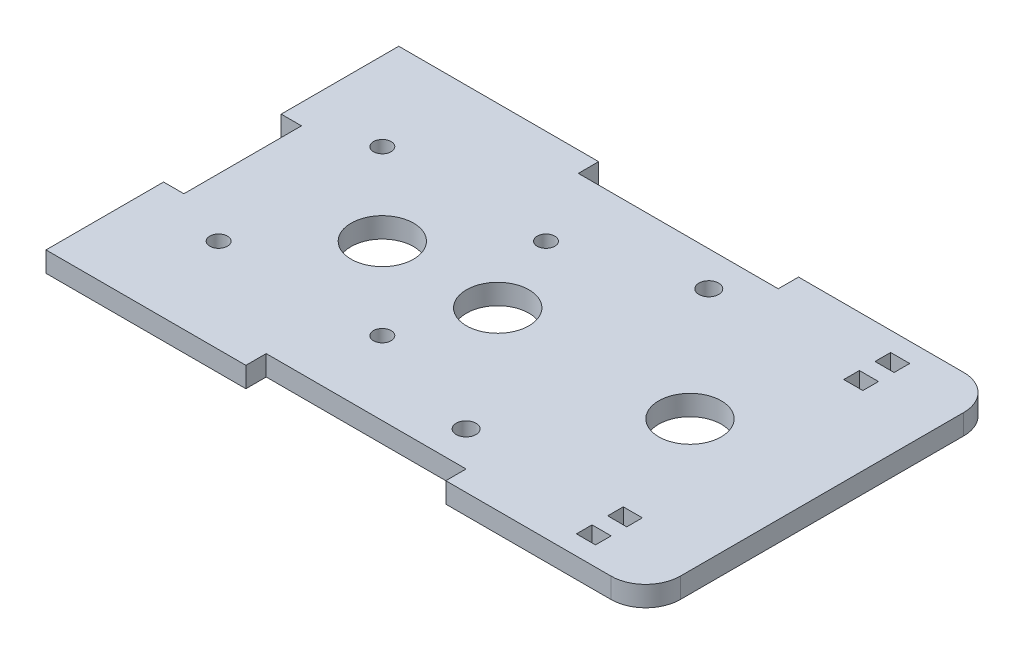
SolidWorks part; units mm, degrees
ref_plane "Front Plane" through (0, 0, 0) normal (0, 0, 1) x (1, 0, 0)
ref_plane "Top Plane" through (0, 0, 0) normal (0, 1, 0) x (1, 0, 0)
ref_plane "Right Plane" through (0, 0, 0) normal (1, 0, 0) x (0, 0, -1)
sketch "Sketch1" plane through (0, 0, 0) normal (0, 1, 0) x (1, 0, 0)
  line L1 (-86.36, -50.8) -> (86.36, -50.8)
  line L2 (-86.36, -50.8) -> (-86.36, 50.8)
  line L3 (-86.36, 50.8) -> (86.36, 50.8)
  line L4 (86.36, -50.8) -> (86.36, 50.8)
  line L5 (-86.36, -50.8) -> (86.36, 50.8) construction
  line L6 (-86.36, 50.8) -> (86.36, -50.8) construction
  point P0 (0, 0)
  dimension "D1" = 172.72
  dimension "D2" = 101.6
extrude "Boss-Extrude1" add sketch "Sketch1" along normal blind 5.85
sketch "Sketch4" plane through (0, 5.85, 0) normal (0, 1, 0) x (1, 0, 0)
  line L0 (-86.36, 50.8) -> (-86.36, -50.8) construction
  line L1 (-86.36, 16.9333) -> (-80.51, 16.9333)
  line L2 (-86.36, 16.9333) -> (-86.36, -16.9333)
  line L3 (-86.36, -16.9333) -> (-80.51, -16.9333)
  line L4 (-80.51, 16.9333) -> (-80.51, -16.9333)
  line L5 (-86.36, -50.8) -> (86.36, -50.8) construction
  line L6 (-28.7867, -50.8) -> (28.7867, -50.8)
  line L7 (-28.7867, -50.8) -> (-28.7867, -44.95)
  line L8 (-28.7867, -44.95) -> (28.7867, -44.95)
  line L9 (28.7867, -50.8) -> (28.7867, -44.95)
  line L10 (86.36, 50.8) -> (-86.36, 50.8) construction
  line L11 (-28.7867, 50.8) -> (28.7867, 50.8)
  line L12 (-28.7867, 50.8) -> (-28.7867, 44.95)
  line L13 (-28.7867, 44.95) -> (28.7867, 44.95)
  line L14 (28.7867, 50.8) -> (28.7867, 44.95)
  line L15 (-28.7867, 44.95) -> (-28.7867, -44.95) construction
  line L16 (28.7867, 44.95) -> (28.7867, -44.95) construction
  line L17 (60.86, 40.75) -> (60.86, -40.75) construction
  line L18 (60.86, 45.25) -> (66.36, 45.25)
  line L19 (60.86, 45.25) -> (60.86, 40.75)
  line L20 (60.86, 40.75) -> (66.36, 40.75)
  line L21 (86.36, -50.8) -> (86.36, 50.8) construction
  line L22 (60.86, -45.25) -> (66.36, -45.25)
  line L23 (60.86, -45.25) -> (60.86, -40.75)
  line L24 (60.86, -40.75) -> (66.36, -40.75)
  line L25 (60.86, -31.75) -> (66.36, -31.75)
  line L26 (60.86, -31.75) -> (60.86, -36.25)
  line L27 (60.86, -36.25) -> (66.36, -36.25)
  line L28 (66.36, -40.75) -> (66.36, -45.25)
  line L29 (66.36, -31.75) -> (66.36, -36.25)
  line L30 (60.86, 36.25) -> (66.36, 36.25)
  line L31 (60.86, 36.25) -> (60.86, 31.75)
  line L32 (66.36, -40.75) -> (66.36, 40.75) construction
  line L33 (60.86, 31.75) -> (66.36, 31.75)
  line L34 (66.36, 36.25) -> (66.36, 31.75)
  line L35 (66.36, 40.75) -> (66.36, 45.25)
  dimension "D1" = 5.85
  dimension "D2" = 5.85
  dimension "D3" = 5.85
  dimension "D4" = 57.5733
  dimension "D5" = 57.5733
  dimension "D6" = 33.8667
  dimension "D7" = 33.8667
  dimension "D8" = 5.5
  dimension "D9" = 5.55
  dimension "D10" = 5.55
  dimension "D11" = 4.5
  dimension "D12" = 4.5
  dimension "D13" = 4.5
  dimension "D14" = 4.5
  dimension "D15" = 4.5
  dimension "D16" = 4.5
  dimension "D17" = 20
extrude "Cut-Extrude5" cut sketch "Sketch4" against normal blind 10
sketch "Sketch5" plane through (0, 0, 0) normal (0, 1, 0) x (1, 0, 0)
  line L0 (-86.36, -0.1894) -> (2.54, -0.1894) construction
  line L2 (2.54, -0.1894) -> (91.44, -0.1894) construction
  line L4 (0, 50.8) -> (0, -50.8) construction
  line L7 (-6.8721, -0.1894) -> (-40.1037, -0.1894) construction
  line L8 (48.5139, -0.1894) -> (-6.8721, -0.1894) construction
  line L9 (-49.1037, -0.1894) -> (-40.1037, -9.1894) construction
  line L10 (-40.1037, -9.1894) -> (-31.1037, -0.1894) construction
  line L11 (-31.1037, -0.1894) -> (-40.1037, 8.8106) construction
  line L12 (-40.1037, 8.8106) -> (-49.1037, -0.1894) construction
  line L13 (-86.36, 16.9333) -> (-86.36, -0.1894) construction
  line L21 (-63.6769, -23.7626) -> (-16.5306, -23.7626) construction
  line L22 (-63.6769, -23.7626) -> (-63.6769, 23.3837) construction
  line L23 (-63.6769, 23.3837) -> (-16.5306, 23.3837) construction
  line L24 (-16.5306, -23.7626) -> (-16.5306, 23.3837) construction
  line L25 (-63.6769, -23.7626) -> (-16.5306, 23.3837) construction
  line L26 (-63.6769, 23.3837) -> (-16.5306, -23.7626) construction
  line L29 (26.7151, -50.8) -> (26.7151, 50.8) construction
  line L30 (-63.6769, 23.3837) -> (-63.6769, 25.9237) construction
  circle A1 centre (-6.8721, -0.1894) radius 9
  circle A2 centre (-40.1037, -0.1894) radius 9
  circle A3 centre (-63.6769, 23.3837) radius 2.54
  circle A4 centre (-16.5306, 23.3837) radius 2.54
  circle A5 centre (-63.6769, -23.7626) radius 2.54
  circle A6 centre (-16.5306, -23.7626) radius 2.54
  circle A7 centre (48.5139, -0.1894) radius 9
  dimension "D1" = 18
  dimension "D2" = 18
  dimension "D3" = 18
  dimension "D5" = 55.386
  dimension "D6" = 33.2317
  dimension "D7" = 46.2563
extrude "Cut-Extrude10" cut sketch "Sketch5" along direction (0, -1, 0) on the side of the normal blind 16
fillet "Fillet1" radius 10 2 edges at (86.36, 2.925, -50.8) (86.36, 2.925, 50.8)
sketch "Sketch6" plane through (0, 5.85, 0) normal (0, 1, 0) x (1, 0, 0)
  line L0 (28.7867, -44.95) -> (28.7867, -34.95) construction
  line L1 (28.7867, -34.95) -> (18.7867, -34.95) construction
  line L2 (28.7867, 44.95) -> (28.7867, 34.95) construction
  line L3 (28.7867, 34.95) -> (18.7867, 34.95) construction
  circle A0 centre (18.7867, -34.95) radius 2.85
  circle A1 centre (18.7867, 34.95) radius 2.85
  dimension "D1" = 5.7
  dimension "D4" = 5.7
  dimension "D2" = 10
  dimension "D3" = 10
  dimension "D5" = 10
  dimension "D6" = 10
extrude "Cut-Extrude11" cut sketch "Sketch6" against normal blind 10
equation "\"D1@Sketch1\" = \"Length@RudderBox.SLDASM\""
equation "\"D2@Sketch1\" = \"Width@RudderBox.SLDASM\""
equation "\"D1@Boss-Extrude1\" = \"Material@RudderBox.SLDASM\""
equation "\"D1@Sketch4\" = \"Material@RudderBox.SLDASM\""
equation "\"D2@Sketch4\" = \"Material@RudderBox.SLDASM\""
equation "\"D3@Sketch4\" = \"Material@RudderBox.SLDASM\""
equation "\"D4@Sketch4\" = \"Length@RudderBox.SLDASM\"/3"
equation "\"D5@Sketch4\" = \"Length@RudderBox.SLDASM\"/3"
equation "\"D6@Sketch4\" = \"Width@RudderBox.SLDASM\"/3"
equation "\"D7@Sketch4\" = \"Width@RudderBox.SLDASM\"/3"
